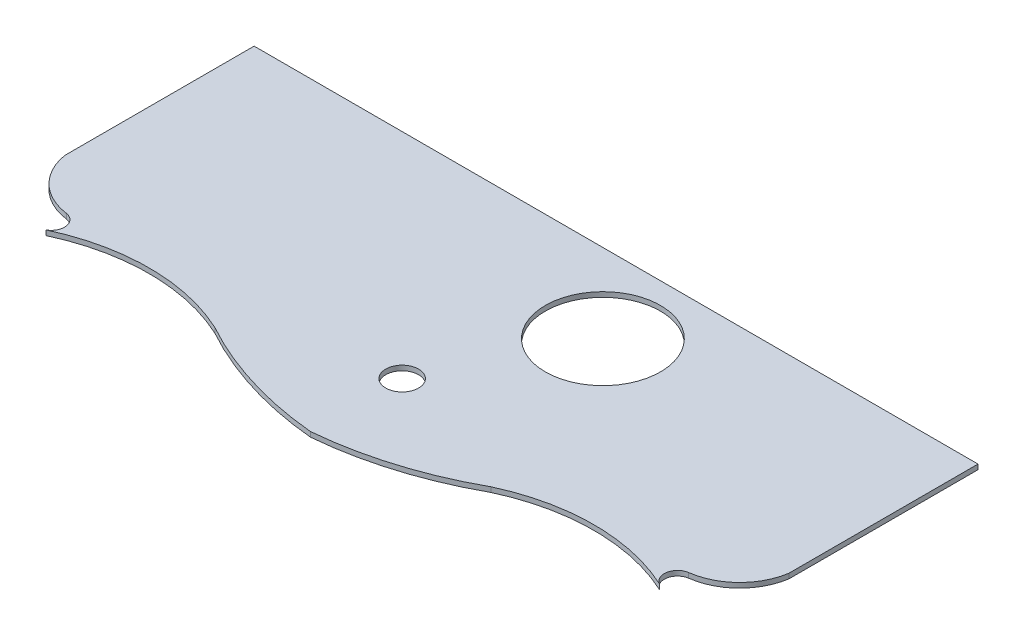
SolidWorks part; units mm, degrees
ref_plane "Front Plane" through (0, 0, 0) normal (0, 0, 1) x (1, 0, 0)
ref_plane "Top Plane" through (0, 0, 0) normal (0, 1, 0) x (1, 0, 0)
ref_plane "Right Plane" through (0, 0, 0) normal (1, 0, 0) x (0, 0, -1)
ref_plane "Plane1" through (0, 4.5, 0) normal (0, 1, 0) x (1, 0, 0)
ref_plane "Plane2" through (0, 3, 0) normal (0, 1, 0) x (1, 0, 0)
sketch "Sketch1" plane through (0, 3, 0) normal (0, 1, 0) x (1, 0, 0)
  line L0 (0, -100) -> (0, 70) construction
  line L5 (-110, 50) -> (-110, -7.5)
  line L18 (0, 0) -> (0, -34.383) construction
  line L19 (-110, 50) -> (110, 50)
  line L22 (110, -7.5) -> (110, 50)
  line L24 (-110, 50) -> (-110, -30) construction
  arc A1 (94.5, -22.5368) -> (93.25, -30) centre (95.1559, -26.4829) ccw
  arc A3 (-110, -7.5) -> (-94.5, -22.5368) centre (-92.222, -4.6815) ccw
  arc A7 (-110, -7.5) -> (-94.5, -22.5368) centre (-92.222, -4.6815) ccw construction
  arc A9 (-94.5, -22.5368) -> (-93.25, -30) centre (-95.1559, -26.4829) cw
  circle A11 centre (0, -15) radius 5
  circle A12 centre (20, 26) radius 17.5
  circle A13 centre (20, 26) radius 17.5 construction
  circle A14 centre (0, -15) radius 5 construction
  arc A15 (-93.25, -30) -> (-94.5, -22.5368) centre (-95.1559, -26.4829) ccw construction
  arc A17 (110, -7.5) -> (94.5, -22.5368) centre (92.222, -4.6815) cw
  arc A18 (93.25, -30) -> (41.9625, -30) centre (67.6063, -85.0296) ccw
  arc A20 (93.25, -30) -> (41.9625, -30) centre (67.6063, -85.0296) ccw construction
  arc A22 (41.9625, -30) -> (0, -42.8761) centre (-9.5248, 62.9793) cw
  arc A23 (0, -42.8761) -> (41.9625, -30) centre (-9.5248, 62.9793) ccw construction
  arc A24 (-41.9625, -30) -> (0, -42.8761) centre (9.5248, 62.9793) ccw
  arc A25 (-41.9625, -30) -> (0, -42.8761) centre (9.5248, 62.9793) ccw construction
  arc A26 (-93.25, -30) -> (-41.9625, -30) centre (-67.6063, -85.0296) cw
  arc A27 (-41.9625, -30) -> (-93.25, -30) centre (-67.6063, -85.0296) ccw construction
extrude "Boss-Extrude1" add sketch "Sketch1" along normal up to surface (1.5 mm away)
